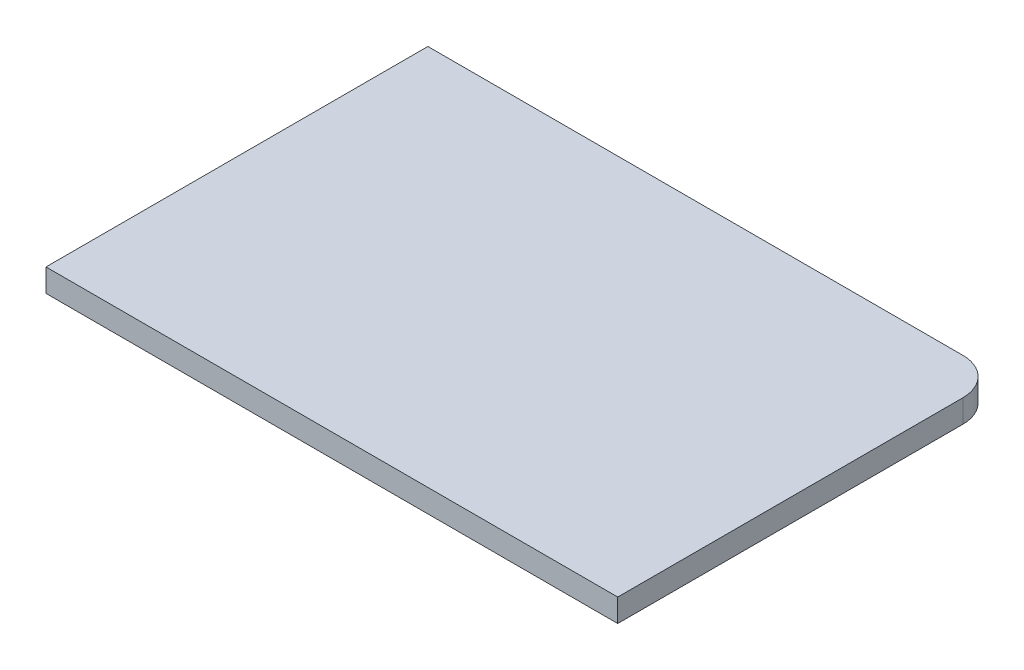
SolidWorks part; units mm, degrees
ref_plane "Alzado" through (0, 0, 0) normal (0, 0, 1) x (1, 0, 0)
ref_plane "Planta" through (0, 0, 0) normal (0, 1, 0) x (1, 0, 0)
ref_plane "Vista lateral" through (0, 0, 0) normal (1, 0, 0) x (0, 0, -1)
sketch "Croquis1" plane through (0, 0, 0) normal (0, 1, 0) x (1, 0, 0)
  line L1 (-62.245, -41.575) -> (62.245, -41.575)
  line L2 (-62.245, -41.575) -> (-62.245, 41.575)
  line L3 (-62.245, 41.575) -> (54.245, 41.575)
  line L4 (62.245, -41.575) -> (62.245, 33.575)
  line L5 (-62.245, -41.575) -> (62.245, 41.575) construction
  line L6 (-62.245, 41.575) -> (62.245, -41.575) construction
  arc A1 (62.245, 33.575) -> (54.245, 41.575) centre (54.245, 33.575) ccw
  point P0 (0, 0)
  dimension "D3" = 8
  dimension "D1" = 124.49
  dimension "D2" = 83.15
extrude "Saliente-Extruir1" add sketch "Croquis1" along normal blind 5
sketch "Croquis2" plane through (0, 0, 0) normal (0, 1, 0) x (1, 0, 0)
  line L0 (52.245, -31.575) -> (52.245, 31.575)
  line L1 (21.4, 31.575) -> (-62.245, 31.575)
  line L3 (-62.245, -31.575) -> (52.245, -31.575)
  line L4 (62.245, -41.575) -> (62.245, 33.575)
  line L5 (54.245, 41.575) -> (-62.245, 41.575)
  line L6 (-62.245, 41.575) -> (-62.245, -41.575)
  line L7 (-62.245, -41.575) -> (62.245, -41.575)
  line L10 (-62.245, 31.575) -> (-62.245, 36.575)
  line L12 (52.245, 31.575) -> (-52.245, 31.575) construction
  line L13 (-52.245, -31.575) -> (72.3127, -31.575) construction
  line L14 (-52.245, 31.575) -> (-52.245, -31.575) construction
  line L15 (-62.245, 41.575) -> (-62.245, -41.575) construction
  line L16 (62.245, 41.575) -> (-62.245, 41.575) construction
  line L17 (62.245, -50.69) -> (62.245, 41.575) construction
  line L18 (-62.245, -41.575) -> (79.1007, -41.575) construction
  line L20 (-62.245, -36.575) -> (57.245, -36.575)
  line L21 (57.245, -36.575) -> (57.245, 28.575)
  line L22 (49.245, 36.575) -> (-62.245, 36.575)
  line L23 (57.245, 36.575) -> (-67.245, 36.575) construction
  line L24 (-67.245, -36.575) -> (76.129, -36.575) construction
  line L25 (-62.245, -36.575) -> (-62.245, -31.575)
  line L26 (-62.245, 31.575) -> (-62.245, -31.575) construction
  line L27 (-67.245, 36.575) -> (-67.245, -36.575) construction
  line L28 (52.245, 31.575) -> (-62.245, 31.575) construction
  line L29 (52.245, -31.5823) -> (52.245, 31.575) construction
  line L30 (21.4, 31.575) -> (52.245, 31.575)
  line L31 (57.245, -44.8252) -> (57.245, 36.575) construction
  line L33 (62.245, -41.575) -> (62.245, 33.575) construction
  line L34 (-62.245, -31.575) -> (72.3127, -31.575) construction
  arc A3 (79.1007, -41.575) -> (62.245, -50.69) centre (62.2785, -30.6094) ccw construction
  arc A6 (62.245, 33.575) -> (54.245, 41.575) centre (54.245, 33.575) ccw
  arc A7 (57.245, 28.575) -> (49.245, 36.575) centre (49.245, 28.575) ccw
  arc A8 (76.129, -36.575) -> (57.245, -44.8252) centre (62.2785, -30.6094) ccw construction
  arc A9 (72.3127, -31.575) -> (52.245, -31.5823) centre (62.2785, -30.6094) ccw construction
  dimension "D4" = 8
  dimension "D3" = 5
  dimension "D2" = 73.15
  dimension "D5" = 5
  dimension "D1" = 0
extrude "Saliente-Extruir2" add sketch "Croquis2" against normal blind 5
